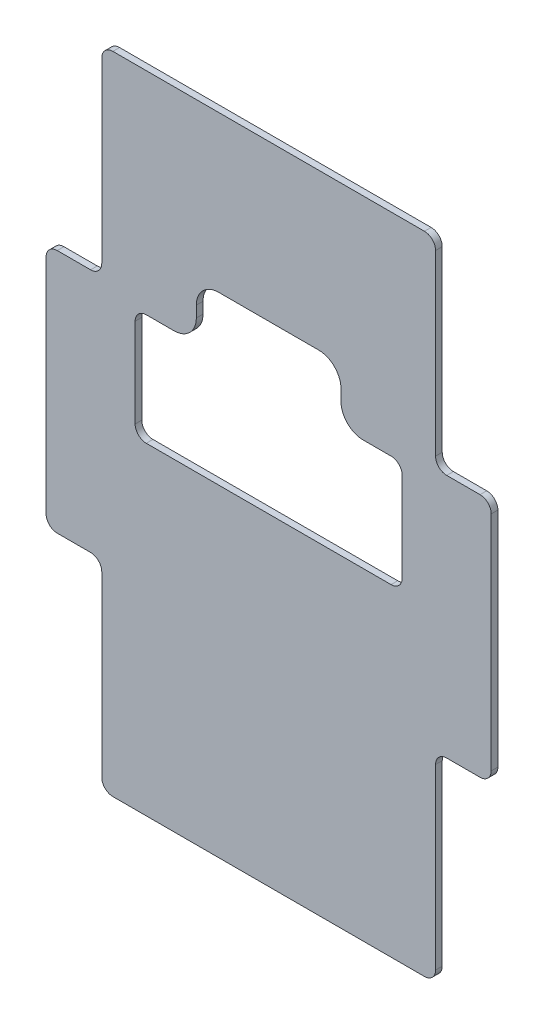
SolidWorks part; units mm, degrees
ref_plane "Front Plane" through (0, 0, 0) normal (0, 0, 1) x (1, 0, 0)
ref_plane "Top Plane" through (0, 0, 0) normal (0, 1, 0) x (1, 0, 0)
ref_plane "Right Plane" through (0, 0, 0) normal (1, 0, 0) x (0, 0, -1)
sketch "Sketch1" plane through (0, 0, 0) normal (0, 0, 1) x (1, 0, 0)
  line L0 (-75, -145) -> (75, -145)
  line L1 (75, -145) -> (75, -55)
  line L2 (75, -55) -> (100, -55)
  line L3 (100, -55) -> (100, 55)
  line L4 (100, 55) -> (75, 55)
  line L5 (75, 55) -> (75, 145)
  line L6 (75, 145) -> (-75, 145)
  line L7 (-75, 145) -> (-75, 55)
  line L8 (-75, 55) -> (-100, 55)
  line L9 (-100, 55) -> (-100, -55)
  line L10 (-100, -55) -> (-75, -55)
  line L11 (-75, -55) -> (-75, -145)
  line L12 (-75, 55) -> (75, 55) construction
  line L13 (75, 55) -> (75, -55) construction
  line L14 (75, -55) -> (-75, -55) construction
  line L15 (-75, -55) -> (-75, 55) construction
  line L16 (0, 55) -> (0, -55) construction
  dimension "D1" = 200
  dimension "D2" = 290
  dimension "D3" = 90
  dimension "D4" = 150
extrude "Boss-Extrude1" add sketch "Sketch1" along normal blind 3
fillet "Fillet1" radius 5 12 edges at (-75, -55, 1.5) (-100, -55, 1.5) (-75, 145, 1.5) (75, 145, 1.5) (75, 55, 1.5) (100, 55, 1.5) (100, -55, 1.5) (75, -55, 1.5) (75, -145, 1.5) (-75, -145, 1.5) (-75, 55, 1.5) (-100, 55, 1.5)
sketch "Sketch13" plane through (0, 0, 0) normal (0, 0, -1) x (-1, 0, 0)
  line L0 (0, 25) -> (0, 0) construction
  line L1 (-55, 50) -> (-42.5, 50)
  line L2 (-60, 45) -> (-60, 5)
  line L3 (-55, 0) -> (55, 0)
  line L4 (60, 45) -> (60, 5)
  line L5 (-60, 50) -> (60, 0) construction
  line L6 (-60, 0) -> (60, 50) construction
  line L7 (42.5, 50) -> (55, 50)
  line L9 (-32.5, 60) -> (-32.5, 65)
  line L10 (-22.5, 75) -> (22.5, 75)
  line L11 (32.5, 60) -> (32.5, 65)
  line L12 (0, 75) -> (0, 25) construction
  arc A0 (-60, 5) -> (-55, 0) centre (-55, 5) ccw
  arc A1 (55, 0) -> (60, 5) centre (55, 5) ccw
  arc A2 (55, 50) -> (60, 45) centre (55, 45) cw
  arc A3 (-55, 50) -> (-60, 45) centre (-55, 45) ccw
  arc A4 (42.5, 50) -> (32.5, 60) centre (42.5, 60) cw
  arc A5 (22.5, 75) -> (32.5, 65) centre (22.5, 65) cw
  arc A6 (-32.5, 65) -> (-22.5, 75) centre (-22.5, 65) cw
  arc A7 (-42.5, 50) -> (-32.5, 60) centre (-42.5, 60) ccw
  point P0 (0, 25)
  point P26 (-32.8604, 50)
  point P27 (0, 0)
  dimension "D5" = 5
  dimension "D1" = 10
  dimension "D2" = 25
  dimension "D3" = 120
  dimension "D4" = 50
  dimension "D6" = 65
extrude "Cut-Extrude8" cut sketch "Sketch13" against normal through all
